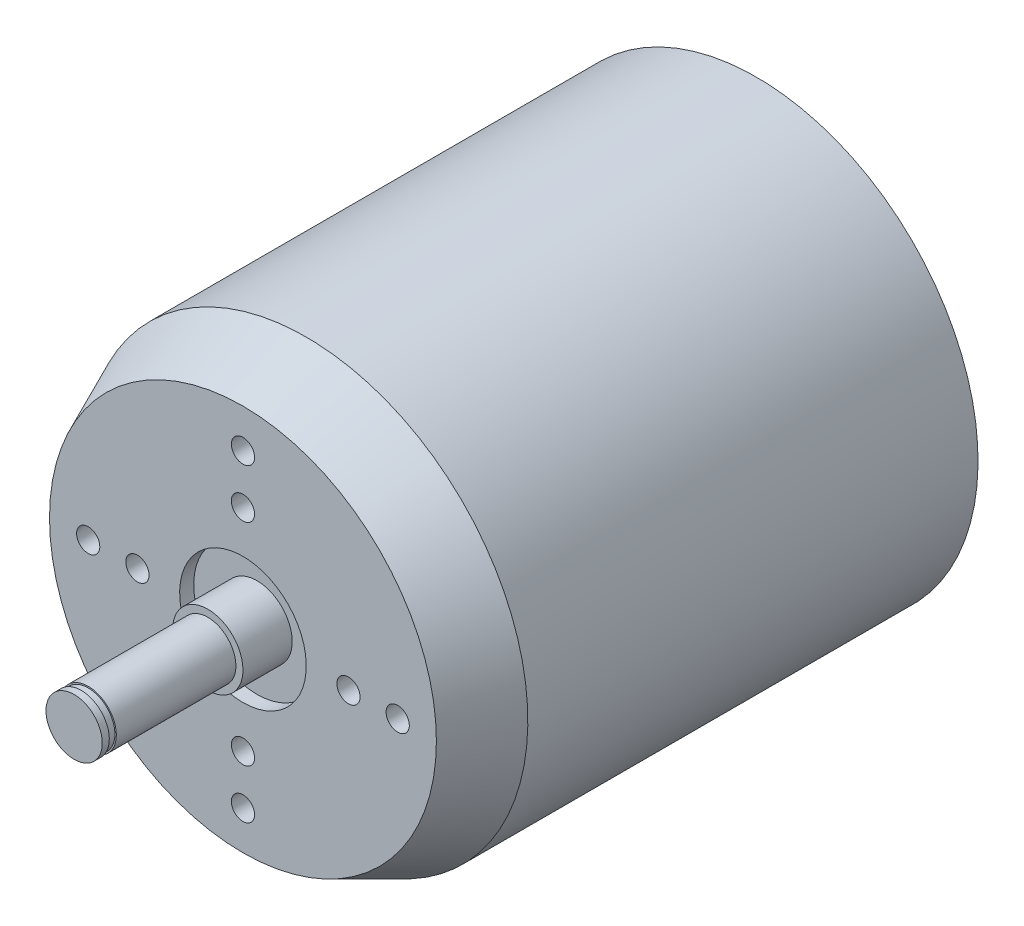
SolidWorks part; units mm, degrees
material "7075-T6 (SN)"
ref_plane "Front Plane" through (0, 0, 0) normal (0, 0, 1) x (1, 0, 0)
ref_plane "Top Plane" through (0, 0, 0) normal (0, 1, 0) x (1, 0, 0)
ref_plane "Right Plane" through (0, 0, 0) normal (1, 0, 0) x (0, 0, -1)
sketch "Sketch2" plane through (0, 0, 0) normal (1, 0, 0) x (0, 0, -1)
  line L1 (0, 27.5) -> (9, 31.5)
  line L2 (9, 31.5) -> (73, 31.5)
  line L3 (73, 31.5) -> (73, 15)
  line L4 (73, 15) -> (74, 15)
  line L5 (74, 15) -> (74, 0)
  line L7 (0, 27.5) -> (0, 9)
  line L8 (0, 9) -> (2, 9)
  line L9 (2, 9) -> (2, 0)
  line L10 (2, 0) -> (74, 0)
  line L11 (2, 5) -> (-5, 5)
  line L12 (-24, 4) -> (-24, 0)
  line L13 (-24, 0) -> (2, 0)
  line L14 (-5, 5) -> (-5, 4)
  line L15 (-5, 4) -> (-22, 4)
  line L16 (-22, 4) -> (-22, 3.8)
  line L17 (-22, 3.8) -> (-23, 3.8)
  line L18 (-23, 3.8) -> (-23, 4)
  line L19 (-23, 4) -> (-24, 4)
  dimension "D1" = 74
  dimension "D2" = 2
  dimension "D3" = 1
  dimension "D4" = 27.5
  dimension "D5" = 15
  dimension "D6" = 65
  dimension "D7" = 31.5
  dimension "D8" = 9
  dimension "D9" = 24
  dimension "D10" = 4
  dimension "D11" = 1
  dimension "D12" = 3.8
  dimension "D13" = 1
  dimension "D14" = 5
  dimension "D15" = 5
revolve "Revolve1" add sketch "Sketch2" angle 360 about L10
sketch "Sketch3" plane through (0, 0, 0) normal (0, 0, 1) x (1, 0, 0)
  circle A0 centre (0, 0) radius 15 construction
  circle A1 centre (0, 0) radius 22 construction
  circle A2 centre (0, 15) radius 2 construction
  circle A3 centre (0, 22) radius 2 construction
  circle A4 centre (22, 0) radius 2 construction
  circle A5 centre (15, 0) radius 2 construction
  circle A6 centre (0, -22) radius 2 construction
  circle A7 centre (0, -15) radius 2 construction
  circle A8 centre (-22, 0) radius 2 construction
  circle A9 centre (-15, 0) radius 2 construction
  point P8 (17.2271, -6.9645)
  point P9 (0, 0)
  point P23 (0, 0)
  dimension "D1" = 44
  dimension "D2" = 30
  dimension "D3" = 4
  dimension "D4" = 4
hole_wizard "Tap Drill for M4x0.7 Tap1" positions "3DSketch1" profile "Sketch4" hole size "M4x0.7" standard "ANSI Metric"
sketch3d "3DSketch1"
  point P0 (0, 22, 0)
  point P2 (0, 15, 0)
  point P4 (15, 0, 0)
  point P6 (22, 0, 0)
  point P8 (0, -15, 0)
  point P10 (0, -22, 0)
  point P12 (-15, 0, 0)
  point P14 (-22, 0, 0)
  point P17 (-15, 0, 0)
  point P19 (-22, 0, 0)
  point P21 (0, 15, 0)
  point P23 (0, 22, 0)
  point P25 (15, 0, 0)
  point P27 (22, 0, 0)
  point P29 (0, -15, 0)
  point P31 (0, -22, 0)
sketch "Sketch4" plane through (0, 22, 0) normal (1, 0, 0) x (0, -1, 0)
  line L0 (0, 0) -> (0, 5.9914)
  line L1 (0, 5.9914) -> (1.65, 5)
  line L2 (1.65, 5) -> (1.65, 0)
  line L5 (1.65, 0) -> (0, 0)
  line L10 (0, 5.9914) -> (-1.65, 5) construction
  line L11 (0, -6.35) -> (0, 107.95) construction
  dimension "Hole Dia." = 3.3
  dimension "Hole Depth" = 5
  dimension "Drill Angle" = 118
